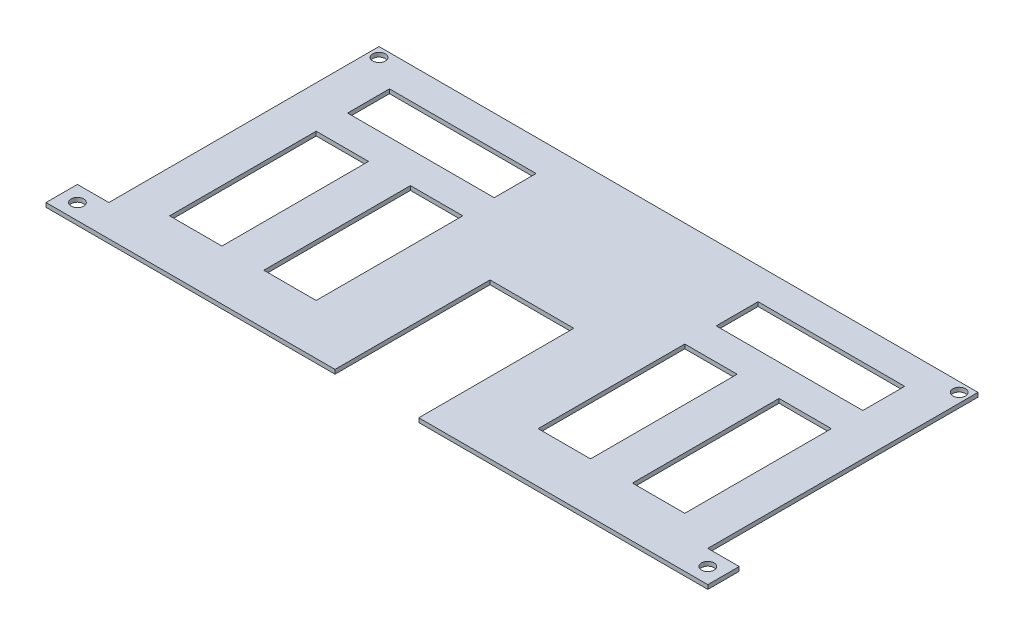
SolidWorks part; units mm, degrees
material "3.3523 (EN-AW 5052)"
ref_plane "Спереди" through (0, 0, 0) normal (0, 0, 1) x (1, 0, 0)
ref_plane "Сверху" through (0, 0, 0) normal (0, 1, 0) x (1, 0, 0)
ref_plane "Справа" through (0, 0, 0) normal (1, 0, 0) x (0, 0, -1)
sketch "Эскиз1" plane through (0, 0, 0) normal (0, 1, 0) x (1, 0, 0)
  line L0 (-143, 72) -> (158, 72)
  line L1 (-143, -72) -> (158, -72)
  line L2 (158, 72) -> (158, -72)
  line L3 (-158, -72) -> (-143, -72)
  line L4 (-158, -72) -> (-158, 72)
  line L5 (-158, 72) -> (-143, 72)
  circle A0 centre (-138.5, 67.5) radius 3
  circle A1 centre (-150.5, -64.5) radius 3
  circle A2 centre (150.5, -64.5) radius 3
  circle A3 centre (138.5, 67.5) radius 3
extrude "Бобышка-Вытянуть1" add sketch "Эскиз1" along normal blind 2
sketch "Эскиз2" plane through (0, 2, 0) normal (0, 1, 0) x (1, 0, 0)
  line L0 (158, -72) -> (158, 72) construction
  line L1 (158, -57) -> (143, -57)
  line L2 (158, -57) -> (158, 72)
  line L3 (158, 72) -> (143, 72)
  line L4 (143, -57) -> (143, 72)
  line L5 (158, 72) -> (-158, 72) construction
  line L6 (-143, 72) -> (-158, 72)
  line L7 (-143, 72) -> (-143, -57)
  line L8 (-143, -57) -> (-158, -57)
  line L9 (-158, 72) -> (-158, -57)
  line L10 (-158, 72) -> (-158, -72) construction
extrude "Вырез-Вытянуть1" cut sketch "Эскиз2" against normal through all
sketch "Эскиз3" plane through (0, 2, 0) normal (0, 1, 0) x (1, 0, 0)
  line L0 (-158, -72) -> (158, -72) construction
  line L1 (20, -72) -> (-20, -72)
  line L2 (20, -72) -> (20, 2)
  line L3 (20, 2) -> (-20, 2)
  line L4 (-20, -72) -> (-20, 2)
  line L5 (20, -54.7424) -> (20, -1.8705) construction
  line L6 (20, -1.8705) -> (-20, -0.8792) construction
  line L7 (-20, -0.8792) -> (-20, -59.6992) construction
  dimension "D1" = 74
extrude "Вырез-Вытянуть2" cut sketch "Эскиз3" against normal through all
sketch "Эскиз4" plane through (0, 2, 0) normal (0, 1, 0) x (1, 0, 0)
  line L0 (143, 72) -> (-143, 72) construction
  line L1 (-123, 57) -> (-53, 57)
  line L2 (-123, 57) -> (-123, 37)
  line L3 (-123, 37) -> (-53, 37)
  line L4 (-53, 57) -> (-53, 37)
  line L5 (-123, 22) -> (-98, 22)
  line L6 (-123, 22) -> (-123, -48)
  line L7 (-123, -48) -> (-98, -48)
  line L8 (-98, 22) -> (-98, -48)
  line L9 (-78, 22) -> (-53, 22)
  line L10 (-78, 22) -> (-78, -48)
  line L11 (-78, -48) -> (-53, -48)
  line L12 (-53, 22) -> (-53, -48)
  line L13 (-143, -57) -> (-143, 72) construction
  line L14 (0, 0) -> (0, 82.28) construction
  line L15 (53, 22) -> (53, -48)
  line L16 (78, -48) -> (53, -48)
  line L17 (78, 22) -> (78, -48)
  line L18 (78, 22) -> (53, 22)
  line L19 (98, 22) -> (98, -48)
  line L20 (123, -48) -> (98, -48)
  line L21 (123, 22) -> (123, -48)
  line L22 (123, 22) -> (98, 22)
  line L23 (53, 57) -> (53, 37)
  line L24 (123, 37) -> (53, 37)
  line L25 (123, 57) -> (123, 37)
  line L26 (123, 57) -> (53, 57)
  dimension "D1" = 20
  dimension "D2" = 70
  dimension "D3" = 25
  dimension "D4" = 15
  dimension "D5" = 15
  dimension "D6" = 20
extrude "Вырез-Вытянуть3" cut sketch "Эскиз4" against normal through all
